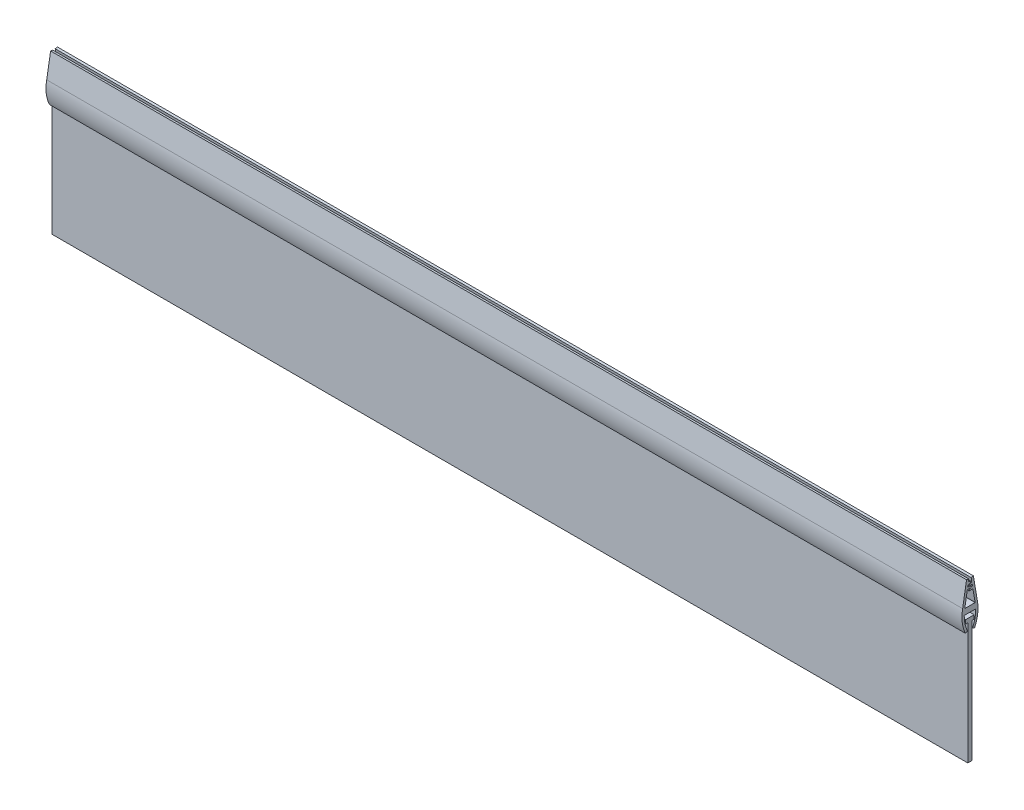
SolidWorks part; units mm, degrees
material "Резина"
ref_plane "Спереди" through (0, 0, 0) normal (0, 0, 1) x (1, 0, 0)
ref_plane "Сверху" through (0, 0, 0) normal (0, 1, 0) x (1, 0, 0)
ref_plane "Справа" through (0, 0, 0) normal (1, 0, 0) x (0, 0, -1)
sketch "Эскиз1" plane through (0, 0, 0) normal (1, 0, 0) x (0, 0, -1)
  line L0 (-1.2, 9.9277) -> (0.5, 20)
  line L1 (2, 25.4452) -> (2, -11.5243) construction
  line L2 (5.2, 9.9277) -> (3.5, 20)
  line L3 (-0.2165, 9.7461) -> (0.8573, 16.1086)
  line L4 (4.2165, 9.7461) -> (3.2928, 15.2187)
  line L5 (2.5139, 19.8336) -> (3.5, 20)
  line L6 (1.4861, 19.8336) -> (0.5, 20)
  line L7 (0, 0) -> (0.9056, 0.4242)
  line L8 (0.9056, 0.4242) -> (0.904, 0.4345)
  line L9 (4, 0) -> (3.0944, 0.4242)
  line L10 (-0.5096, 7) -> (4.5096, 7)
  line L11 (-0.2639, 9.5) -> (4.2639, 9.5)
  line L12 (3.2928, 15.2187) -> (1.5999, 15.2187)
  line L13 (1.5999, 15.2187) -> (1.5999, 15.7584)
  line L14 (2.9611, 17.1844) -> (1.5999, 16.9547)
  line L15 (1.5999, 15.7584) -> (3.0944, 16.3942)
  line L16 (1.5999, 16.9547) -> (1.5999, 17.4607)
  line L17 (1.5999, 17.4607) -> (2.8003, 18.1372)
  line L18 (0.8573, 16.1086) -> (2.3506, 16.1086)
  line L19 (2.3506, 16.1086) -> (2.3506, 16.7738)
  line L20 (2.3506, 16.7738) -> (1.0079, 17.0004)
  line L21 (1.1291, 17.7189) -> (2.2858, 17.9483)
  line L22 (2.2858, 17.9483) -> (2.2858, 18.4486)
  line L23 (2.2858, 18.4486) -> (1.3182, 18.8388)
  line L24 (1.3182, 18.8388) -> (1.4861, 19.8336)
  line L25 (1.0079, 17.0004) -> (1.1291, 17.7189)
  line L26 (-0.2165, 9.7461) -> (1.4861, 19.8336) construction
  line L27 (2.8003, 18.1372) -> (2.5139, 19.8336)
  line L28 (3.0944, 16.3942) -> (2.9611, 17.1844)
  line L29 (4.2165, 9.7461) -> (2.5139, 19.8336) construction
  arc A0 (0, 0) -> (-1.2, 9.9277) centre (14.4889, 6.7877) cw
  arc A1 (4, 0) -> (5.2, 9.9277) centre (-10.4889, 6.7877) ccw
  arc A2 (0.9056, 0.4242) -> (-0.5096, 7) centre (14.4889, 6.7877) cw
  arc A3 (3.0944, 0.4242) -> (4.5096, 7) centre (-10.4889, 6.7877) ccw
  arc A4 (-0.2639, 9.5) -> (-0.2165, 9.7461) centre (14.4889, 6.7877) cw
  arc A5 (4.2639, 9.5) -> (4.2165, 9.7461) centre (-10.4889, 6.7877) ccw
  arc A6 (0.9056, 0.4242) -> (-0.2165, 9.7461) centre (14.4889, 6.7877) cw construction
  arc A8 (3.0944, 0.4242) -> (4.2165, 9.7461) centre (-10.4889, 6.7877) ccw construction
  dimension "D4" = 16
  dimension "D1" = 2
  dimension "D2" = 10
  dimension "D3" = 20
  dimension "D5" = 1.5
  dimension "D6" = 3.2
  dimension "D9" = 2.5
  dimension "D10" = 7
  dimension "D7" = 1
  dimension "D8" = 1
extrude "Бобышка-Вытянуть2" add sketch "Эскиз1" along normal mid plane 400 contours A2 L10 A3 L9 A1 L2 L5 L27 L17 L16 L14 L28 L15 L13 L12 L4 A5 L11 A4 L3 L18 L19 L20 L25 L21 L22 L23 L24 L6 L0 A0 L7
sketch "Эскиз2" plane through (200, 0, 0) normal (1, 0, 0) x (0, 0, -1)
  line L1 (0.1122, 5.1044) -> (3.8701, 5.1044)
  line L2 (0.1122, 5.1044) -> (0.1122, 3.4257)
  line L3 (0.1122, 3.4257) -> (3.8701, 3.4257)
  line L4 (3.8701, 5.1044) -> (3.8701, 3.4257)
extrude "Бобышка-Вытянуть3" add sketch "Эскиз2" against normal up to surface (400 mm away) separate body up to face at (-200, 13.2432, -2.0042)
sketch "Эскиз3" plane through (-200, 0, 0) normal (-1, 0, 0) x (0, 0, 1)
  line L0 (-0.1122, 3.4257) -> (-3.8701, 3.4257) construction
  line L1 (-2.9183, 3.4257) -> (-1.0564, 3.4257)
  line L2 (-2.9183, 3.4257) -> (-2.9183, -49.5743)
  line L3 (-2.9183, -49.5743) -> (-1.0564, -49.5743)
  line L4 (-1.0564, 3.4257) -> (-1.0564, -49.5743)
  dimension "D1" = 53
extrude "Бобышка-Вытянуть4" add sketch "Эскиз3" against normal up to surface (400 mm away) up to face at (200, 13.2432, -2.0042)
